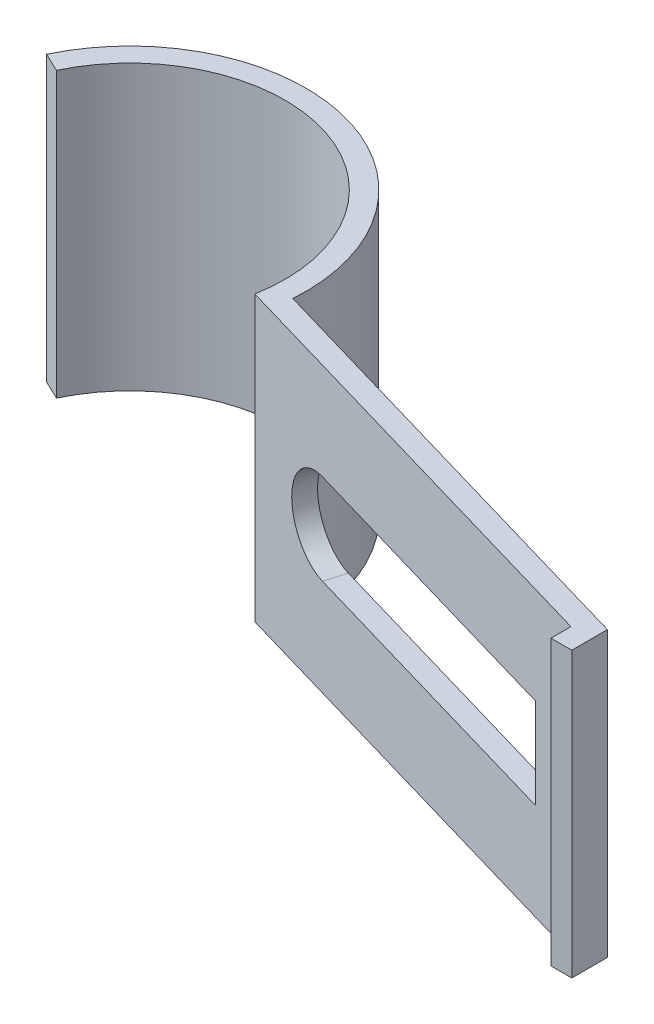
SolidWorks part; units mm, degrees
ref_plane "Front Plane" through (0, 0, 0) normal (0, 0, 1) x (1, 0, 0)
ref_plane "Top Plane" through (0, 0, 0) normal (0, 1, 0) x (1, 0, 0)
ref_plane "Right Plane" through (0, 0, 0) normal (1, 0, 0) x (0, 0, -1)
sketch "Sketch1" plane through (0, 0, 0) normal (0, 1, 0) x (1, 0, 0)
  line L0 (0, 0) -> (0, 0.4) construction
  line L1 (0, 0.4) -> (-6.3939, 2.2637) construction
  line L2 (-4.4506, 0) -> (4.782, 0) construction
  line L3 (-6.3939, 2.2637) -> (-10.9062, 3.5789) construction
  line L4 (-8.65, 2.9213) -> (-8.0904, 4.8414) construction
  line L5 (0.15, 0) -> (0.15, 0.5125)
  line L6 (0.15, 0.5125) -> (-6.2326, 2.3729)
  line L7 (-0.15, 0) -> (-0.15, 0.2875)
  line L8 (-0.15, 0.2875) -> (-6.562, 2.1564)
  line L9 (0.15, 0) -> (-0.15, 0)
  line L10 (-11.0416, 3.6433) -> (-10.7707, 3.5144)
  arc A0 (-6.3939, 2.2637) -> (-10.9062, 3.5789) centre (-8.7566, 2.5558) ccw construction
  arc A1 (-6.2326, 2.3729) -> (-11.0416, 3.6433) centre (-8.7566, 2.5558) ccw
  arc A2 (-6.562, 2.1564) -> (-10.7707, 3.5144) centre (-8.7566, 2.5558) ccw
  point P10 (-8.0904, 4.8414)
  dimension "D1" = 0.4
  dimension "D2" = 6.66
  dimension "D3" = 16.25
  dimension "D4" = 4.7
  dimension "D5" = 2
  dimension "D6" = 0.15
  dimension "D7" = 0.15
extrude "Boss-Extrude1" add sketch "Sketch1" along normal blind 4.08
sketch "Sketch2" plane through (0.1494, 0, -0.5127) normal (0.2798, 0, -0.96) x (-0.96, 0, -0.2798)
  line L0 (-0.0006, 2.04) -> (6.6476, 2.04) construction
  line L1 (-0.0006, 4.08) -> (-0.0006, 0) construction
  line L2 (6.6476, 4.08) -> (6.6476, 0) construction
  line L3 (0.9735, 1.39) -> (0.9735, 2.69)
  line L4 (0.9735, 2.69) -> (5.4735, 2.69)
  line L5 (0.9735, 1.39) -> (5.4735, 1.39)
  arc A0 (5.4735, 2.69) -> (5.4735, 1.39) centre (5.4735, 2.04) cw
  point P6 (5.4699, 2.69)
  point P11 (0, 0)
  point P13 (0.9735, 2.04)
  dimension "D1" = 1.3
  dimension "D2" = 4.5
  dimension "D3" = 0.9741
extrude "Cut-Extrude1" cut sketch "Sketch2" against normal up to surface (0.3 mm away) up to face at (-3.356, 2.04, -1.2219)
